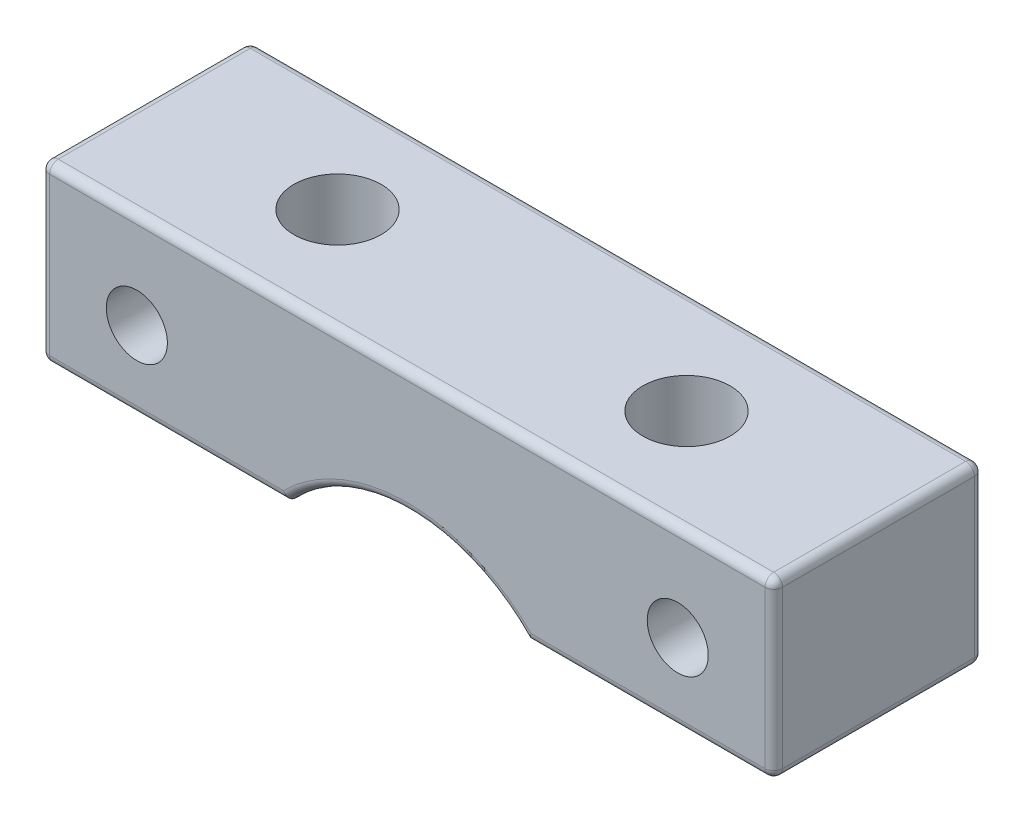
SolidWorks part; units mm, degrees
ref_plane "Alzado" through (0, 0, 0) normal (0, 0, 1) x (1, 0, 0)
ref_plane "Planta" through (0, 0, 0) normal (0, 1, 0) x (1, 0, 0)
ref_plane "Vista lateral" through (0, 0, 0) normal (1, 0, 0) x (0, 0, -1)
ref_plane "Plano1" through (0, 0, 0) normal (0, -1, 0) x (1, 0, 0)
sketch "Croquis1" plane through (0, 0, 0) normal (0, -1, 0) x (1, 0, 0)
  line L0 (-21, 0) -> (21, 0)
  line L1 (21, 0) -> (21, 12)
  line L2 (21, 12) -> (-21, 12)
  line L3 (-21, 12) -> (-21, 0)
extrude "Saliente-Extruir1" add sketch "Croquis1" against normal blind 10
sketch "Croquis2" plane through (0, 0, 0) normal (0, 0, -1) x (-1, 0, 0)
  line L0 (-6.8836, 0) -> (6.8836, 0)
  arc A0 (6.8836, 0) -> (-6.8836, 0) centre (0, -6.5472) ccw
extrude "Cortar-Extruir1" cut sketch "Croquis2" against normal through all
hole_wizard "Diámetro de taladro Ø5.0 (5)1" positions "Croquis4" profile "Croquis3" hole size "Ø5.0" standard "Ansi Metric"
sketch "Croquis4" plane through (0, 0, 0) normal (0, -1, 0) x (-1, 0, 0)
  point P0 (10, -6)
  point P1 (-10, -6)
sketch "Croquis3" plane through (-10, 0, 6) normal (1, 0, 0) x (0, 0, -1)
  line L0 (0, 0) -> (0, 10)
  line L1 (0, 10) -> (2.5, 10)
  line L2 (2.5, 10) -> (2.5, 3)
  line L3 (2.5, 3) -> (5.5, 0)
  line L5 (5.5, 0) -> (0, 0)
  line L6 (-2.5, 3) -> (-5.5, 0) construction
  line L11 (0, -6.35) -> (0, 107.95) construction
  dimension "Diámetro de taladro hasta el siguiente" = 5
  dimension "Profundidad de taladro hasta el siguiente" = 10
  dimension "Diámetro de avellanado cercano" = 11
  dimension "Ángulo de avellanado cercano" = 90
hole_wizard "Diámetro de taladro Ø3.5 (3.5)1" positions "Croquis6" profile "Croquis5" hole size "Ø3.5" standard "Ansi Metric"
sketch "Croquis6" plane through (0, 0, 0) normal (0, 0, -1) x (-1, 0, 0)
  point P0 (15.5, 4.5)
  point P1 (-15.5, 4.5)
sketch "Croquis5" plane through (-15.5, 4.5, 0) normal (1, 0, 0) x (0, 1, 0)
  line L0 (0, 0) -> (0, 12)
  line L1 (0, 12) -> (1.75, 12)
  line L2 (1.75, 12) -> (1.75, 0)
  line L5 (1.75, 0) -> (0, 0)
  line L11 (0, -6.35) -> (0, 107.95) construction
  dimension "Diámetro de taladro hasta el siguiente" = 3.5
  dimension "Profundidad de taladro hasta el siguiente" = 12
fillet "Redondeo1" radius 0.5 16 edges at (13.9418, 0, 12) (0, 2.9528, 0) (0, 2.9528, 12) (21, 0, 6) (13.9418, 0, 0) (21, 5, 12) (-13.9418, 0, 0) (-13.9418, 0, 12) (-21, 0, 6) (21, 5, 0) (21, 10, 6) (0, 10, 12) (-21, 5, 0) (-21, 5, 12) (0, 10, 0) (-21, 10, 6)
